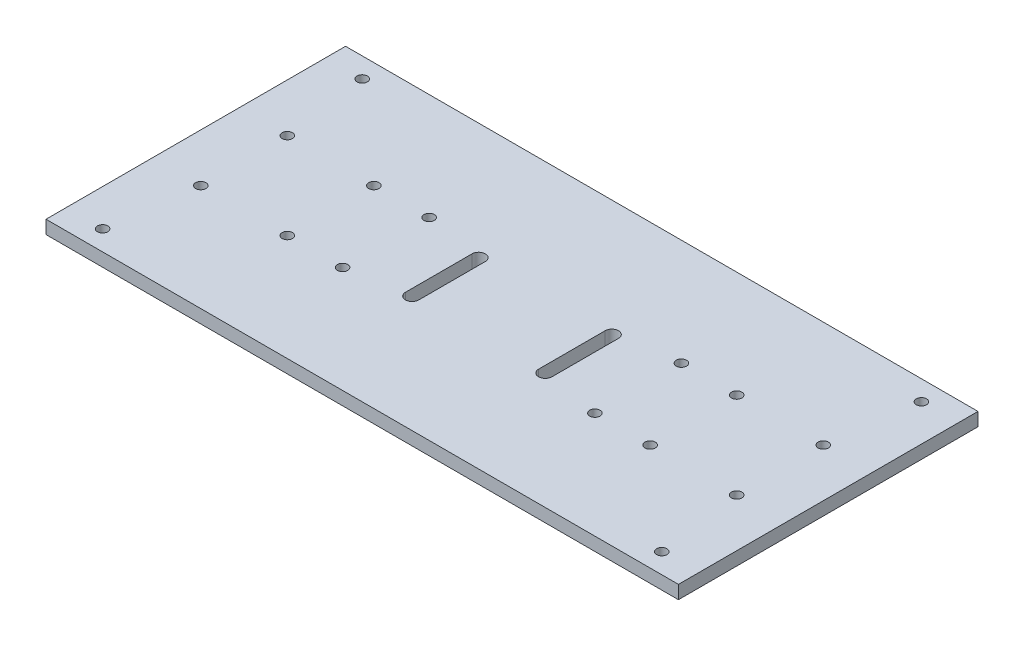
SolidWorks part; units mm, degrees
ref_plane "前视基准面" through (0, 0, 0) normal (0, 0, 1) x (1, 0, 0)
ref_plane "上视基准面" through (0, 0, 0) normal (0, 1, 0) x (1, 0, 0)
ref_plane "右视基准面" through (0, 0, 0) normal (1, 0, 0) x (0, 0, -1)
sketch "草图1" plane through (0, 0, 0) normal (0, 1, 0) x (1, 0, 0)
  line L0 (0, 45) -> (180, 45) construction
  line L1 (0, 0) -> (180, 0)
  line L2 (0, 0) -> (0, 90)
  line L3 (0, 90) -> (180, 90)
  line L4 (180, 0) -> (180, 90)
  line L5 (90, 90) -> (90, 0) construction
  line L6 (22.5, 90) -> (22.5, 0) construction
  line L7 (22.5, 45) -> (9.5, 58) construction
  line L9 (70, 35) -> (70, 55) construction
  line L10 (68, 35) -> (68, 55)
  line L11 (72, 35) -> (72, 55)
  line L12 (110, 35) -> (110, 55) construction
  line L13 (112, 35) -> (112, 55)
  line L14 (108, 35) -> (108, 55)
  circle A0 centre (9.5, 58) radius 1.55
  circle A1 centre (35.5, 58) radius 1.55
  circle A2 centre (35.5, 32) radius 1.55
  circle A3 centre (9.5, 32) radius 1.55
  circle A4 centre (144.5, 58) radius 1.55
  circle A5 centre (170.5, 58) radius 1.55
  circle A6 centre (170.5, 32) radius 1.55
  circle A7 centre (144.5, 32) radius 1.55
  circle A8 centre (127.9, 58) radius 1.55
  circle A12 centre (174, 84) radius 1.55
  circle A13 centre (174, 6) radius 1.55
  circle A14 centre (6, 6) radius 1.55
  circle A15 centre (6, 84) radius 1.55
  arc A16 (68, 35) -> (72, 35) centre (70, 35) ccw
  arc A17 (72, 55) -> (68, 55) centre (70, 55) ccw
  arc A18 (112, 35) -> (108, 35) centre (110, 35) cw
  arc A19 (108, 55) -> (112, 55) centre (110, 55) cw
  circle A20 centre (52.1, 58) radius 1.55
  circle A21 centre (127.9, 32) radius 1.55
  circle A22 centre (52.1, 32) radius 1.55
  point P13 (22.5, 45)
  point P14 (90, 45)
  point P50 (70, 45)
  point P58 (110, 45)
  dimension "D3" = 3.1
  dimension "D10" = 3.1
  dimension "D14" = 13
  dimension "D16" = 3.1
  dimension "D12" = 37.9
  dimension "D1" = 90
  dimension "D2" = 180
  dimension "D4" = 9.5
  dimension "D5" = 13
  dimension "D6" = 13
  dimension "D8" = 18.3848
  dimension "D9" = 13
  dimension "D17" = 6
  dimension "D18" = 6
  dimension "D19" = 4
  dimension "D20" = 20
  dimension "D21" = 20
  dimension "D7" = 4
extrude "凸台-拉伸1" add sketch "草图1" along normal blind 4
ref_plane "基准面1" through (0, 0, 0) normal (0, -1, 0) x (-1, 0, 0)
ref_plane "基准面2" through (0, 0, 0) normal (-1, 0, 0) x (0, 0, 1)
sketch "草图3" plane through (0, 0, 0) normal (-1, 0, 0) x (0, 0, 1)
  line L1 (-90, 4) -> (0, 4)
  line L2 (-90, 4) -> (-90, 0)
  line L3 (-90, 0) -> (0, 0)
  line L4 (0, 4) -> (0, 0)
extrude "凸台-拉伸2" add sketch "草图3" along normal blind 5
ref_plane "基准面4" through (180, 0, 0) normal (1, 0, 0) x (0, 0, -1)
sketch "草图4" plane through (180, 0, 0) normal (1, 0, 0) x (0, 0, -1)
  line L1 (0, 0) -> (90, 0)
  line L2 (0, 0) -> (0, 4)
  line L3 (0, 4) -> (90, 4)
  line L4 (90, 0) -> (90, 4)
extrude "凸台-拉伸3" add sketch "草图4" along normal blind 5
